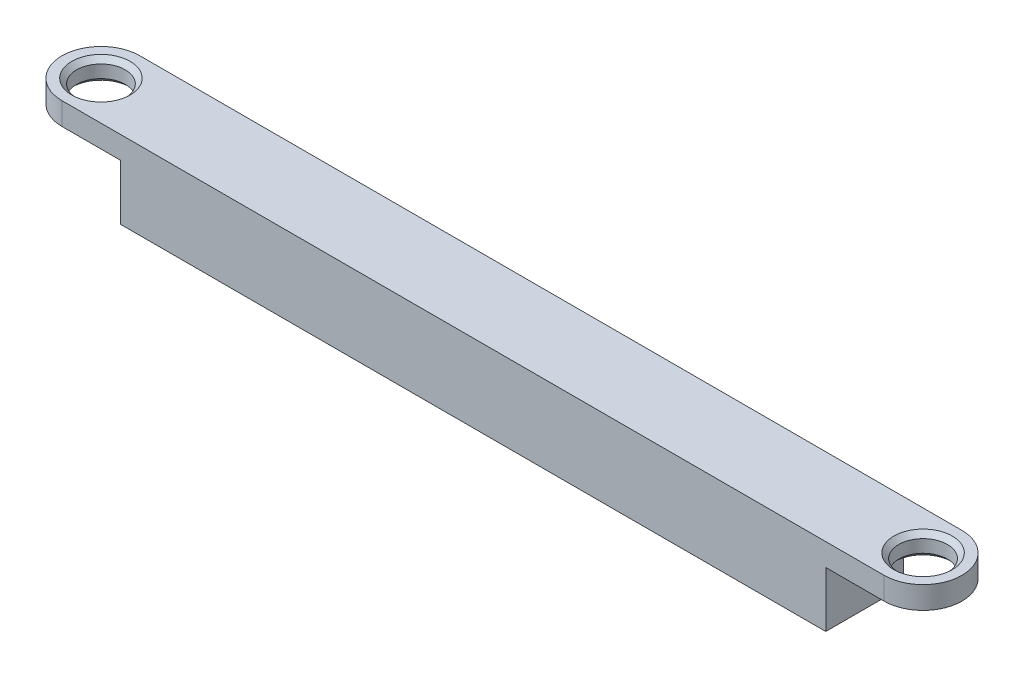
SolidWorks part; units mm, degrees
material "6061-T6 (SS)"
ref_plane "Front" through (0, 0, 0) normal (0, 0, 1) x (1, 0, 0)
ref_plane "Top" through (0, 0, 0) normal (0, 1, 0) x (1, 0, 0)
ref_plane "Right" through (0, 0, 0) normal (1, 0, 0) x (0, 0, -1)
sketch "Sketch1" plane through (0, 0, 0) normal (0, 0, 1) x (1, 0, 0)
  line L1 (-36.25, -4) -> (36.25, -4)
  line L2 (-36.25, -4) -> (-36.25, 4)
  line L3 (-36.25, 4) -> (36.25, 4)
  line L4 (36.25, -4) -> (36.25, 4)
  line L5 (-36.25, -4) -> (36.25, 4) construction
  line L6 (-36.25, 4) -> (36.25, -4) construction
  point P0 (0, 0)
  dimension "D1" = 8
  dimension "D2" = 72.5
extrude "Boss-Extrude1" add sketch "Sketch1" along normal blind 8
sketch "Sketch2" plane through (0, -4, 0) normal (0, -1, 0) x (1, 0, 0)
  line L0 (0, 0) -> (0, 17.7165) construction
  line L1 (-0.25, 0) -> (-4.25, 0)
  line L2 (-36.25, 0) -> (36.25, 0) construction
  dimension "D1" = 4
  dimension "D2" = 0.25
extrude "Extrude-Thin1" add sketch "Sketch2" along normal blind 1 thin
pattern_linear "LPattern1" count 8 spacing 4.5 along (-1, 0, 0) count 9 spacing 4.5 along (1, 0, 0) of "Extrude-Thin1"
sketch "Sketch3" plane through (36.25, 0, 0) normal (1, 0, 0) x (0, 0, -1)
  line L1 (-8, 4) -> (0, 4)
  line L2 (-8, 4) -> (-8, 1.7)
  line L3 (-8, 1.7) -> (0, 1.7)
  line L4 (0, 4) -> (0, 1.7)
  line L5 (0, -4) -> (0, 4) construction
  line L6 (-8, -4) -> (0, -4) construction
  dimension "D1" = 5.7
  dimension "D2" = 8
extrude "Boss-Extrude2" add sketch "Sketch3" along normal blind 12
mirror "Mirror1" about plane through (0, 0, 0) normal (1, 0, 0) of "Boss-Extrude2"
sketch "Sketch4" plane through (0, 4, 0) normal (0, 1, 0) x (1, 0, 0)
  line L0 (-46.5, -4) -> (49953.5, -4) construction
  line L1 (-48.25, 0) -> (-48.25, -8) construction
  line L2 (0, 0) -> (0, 50000) construction
  line L3 (48.25, 0) -> (-48.25, 0) construction
  line L4 (-42.25, 0) -> (42.25, 0)
  line L5 (42.25, -8) -> (-42.25, -8)
  circle A0 centre (-42.25, -4) radius 2.5
  circle A1 centre (42.25, -4) radius 2.5
  arc A2 (-42.25, 0) -> (-42.25, -8) centre (-42.25, -4) ccw
  arc A3 (42.25, -8) -> (42.25, 0) centre (42.25, -4) ccw
  point P4 (-48.25, -4)
  dimension "D1" = 5
  dimension "D2" = 84.5
extrude "Cut-Extrude1" cut sketch "Sketch4" against normal through all flip side to cut
sketch "Sketch5" plane through (0, -4, 0) normal (0, -1, 0) x (1, 0, 0)
  line L1 (-37.4193, 8) -> (37.6585, 8)
  line L2 (-37.4193, 8) -> (-37.4193, 1)
  line L4 (37.6585, 8) -> (37.6585, 1)
  line L6 (37.6585, 1) -> (-37.4193, 1)
sketch "Sketch6" plane through (0, -5, 0) normal (0, -1, 0) x (1, 0, 0)
  line L2 (42.25, 8) -> (-42.25, 8)
  line L3 (-42.25, 0) -> (42.25, 0)
  line L4 (42.25, 8) -> (-42.25, 8)
  line L5 (-42.25, 0) -> (42.25, 0)
  arc A2 (-42.25, 8) -> (-42.25, 0) centre (-42.25, 4) ccw
  arc A3 (42.25, 0) -> (42.25, 8) centre (42.25, 4) ccw
  arc A4 (-42.25, 8) -> (-42.25, 0) centre (-42.25, 4) ccw
  arc A5 (42.25, 0) -> (42.25, 8) centre (42.25, 4) ccw
  dimension "D1" = 0
sketch "Sketch7" [suppressed] plane through (0, 0, 0) normal (0, 1, 0) x (1, 0, 0)
  line L0 (42.25, -8) -> (-42.25, -8) construction
  line L1 (-37.5, -6) -> (37.5, -6)
  line L2 (-37.5, -6) -> (-37.5, -8)
  line L3 (-37.5, -8) -> (37.5, -8)
  line L4 (37.5, -6) -> (37.5, -8)
  line L5 (-37.5, -6) -> (37.5, -8) construction
  line L6 (-37.5, -8) -> (37.5, -6) construction
  point P0 (0, -7)
  dimension "D1" = 2
  dimension "D2" = 75
extrude "Cut-Extrude2" [suppressed] cut sketch "Sketch7" against normal through all both and the other way through all
sketch "Sketch8" [suppressed] plane through (0, 0, 0) normal (0, 1, 0) x (1, 0, 0)
  line L0 (42.25, -8) -> (-42.25, -8) construction
  line L1 (-37.5, -4.5) -> (37.5, -4.5)
  line L2 (-37.5, -4.5) -> (-37.5, -8)
  line L3 (-37.5, -8) -> (37.5, -8)
  line L4 (37.5, -4.5) -> (37.5, -8)
  line L5 (-37.5, -4.5) -> (37.5, -8) construction
  line L6 (-37.5, -8) -> (37.5, -4.5) construction
  line L7 (42.25, 0) -> (-42.25, 0) construction
  point P0 (0, -6.25)
  dimension "D1" = 75
  dimension "D2" = 4.5
extrude "Cut-Extrude3" [suppressed] cut sketch "Sketch8" against normal through all both and the other way through all
chamfer "Chamfer1" distance 0.5 angle 45 4 edges at (-42.25, 4, 6.5) (-42.25, 1.7, 1.5) (42.25, 1.7, 6.5) (42.25, 4, 1.5)
fillet "Fillet1" [suppressed] radius 1
